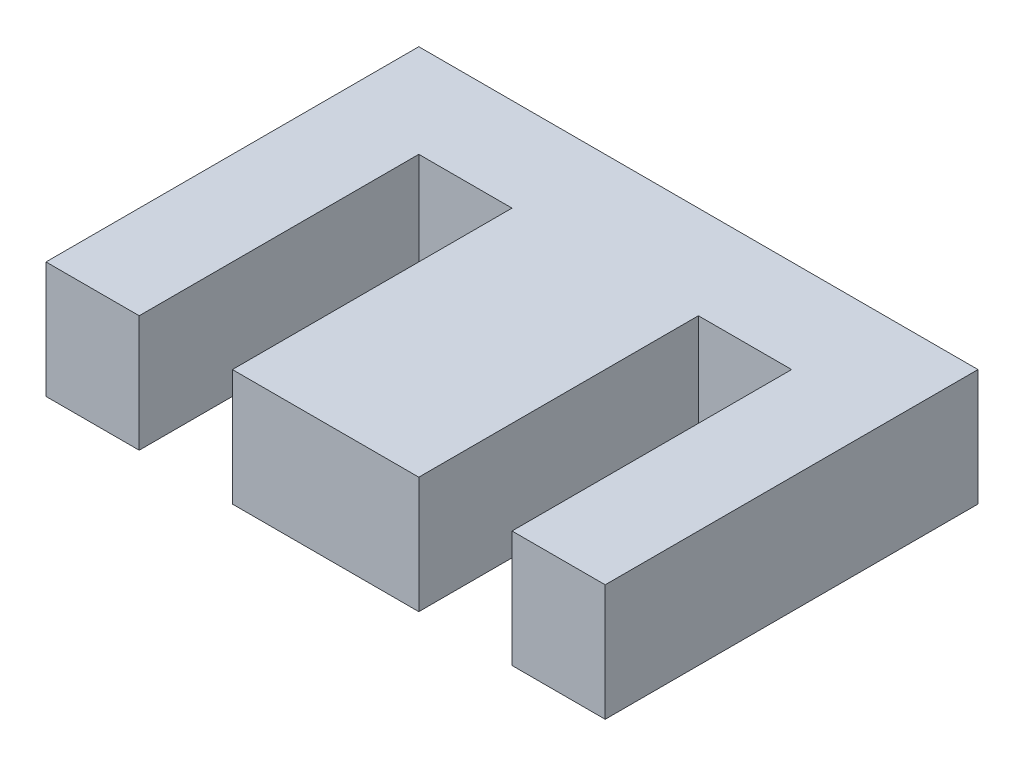
SolidWorks part; units mm, degrees
ref_plane "Front Plane" through (0, 0, 0) normal (0, 0, 1) x (1, 0, 0)
ref_plane "Top Plane" through (0, 0, 0) normal (0, 1, 0) x (1, 0, 0)
ref_plane "Right Plane" through (0, 0, 0) normal (1, 0, 0) x (0, 0, -1)
sketch "Sketch1" plane through (0, 0, 0) normal (0, 1, 0) x (1, 0, 0)
  line L0 (0, 16) -> (0, -16) construction
  line L1 (-24, -16) -> (-16, -16)
  line L2 (-24, -16) -> (-24, 16)
  line L3 (-24, 16) -> (24, 16)
  line L4 (24, -16) -> (24, 16)
  line L5 (-24, -16) -> (24, 16) construction
  line L6 (-24, 16) -> (24, -16) construction
  line L7 (16, -16) -> (24, -16)
  line L8 (-16, -16) -> (-16, 8)
  line L9 (-16, 8) -> (-8, 8)
  line L10 (-8, -16) -> (-8, 8)
  line L11 (8, -16) -> (8, 8)
  line L12 (16, 8) -> (8, 8)
  line L13 (16, -16) -> (16, 8)
  line L14 (-8, -16) -> (8, -16)
  point P0 (0, 0)
  dimension "D1" = 48
  dimension "D2" = 32
  dimension "D3" = 8
  dimension "D4" = 8
  dimension "D5" = 16
extrude "Boss-Extrude1" add sketch "Sketch1" along normal blind 10
sketch "Sketch2" plane through (0, 0, -8) normal (0, 0, 1) x (1, 0, 0)
  line L0 (8, 10) -> (-8, 0) construction
  point P6 (0, 5)
